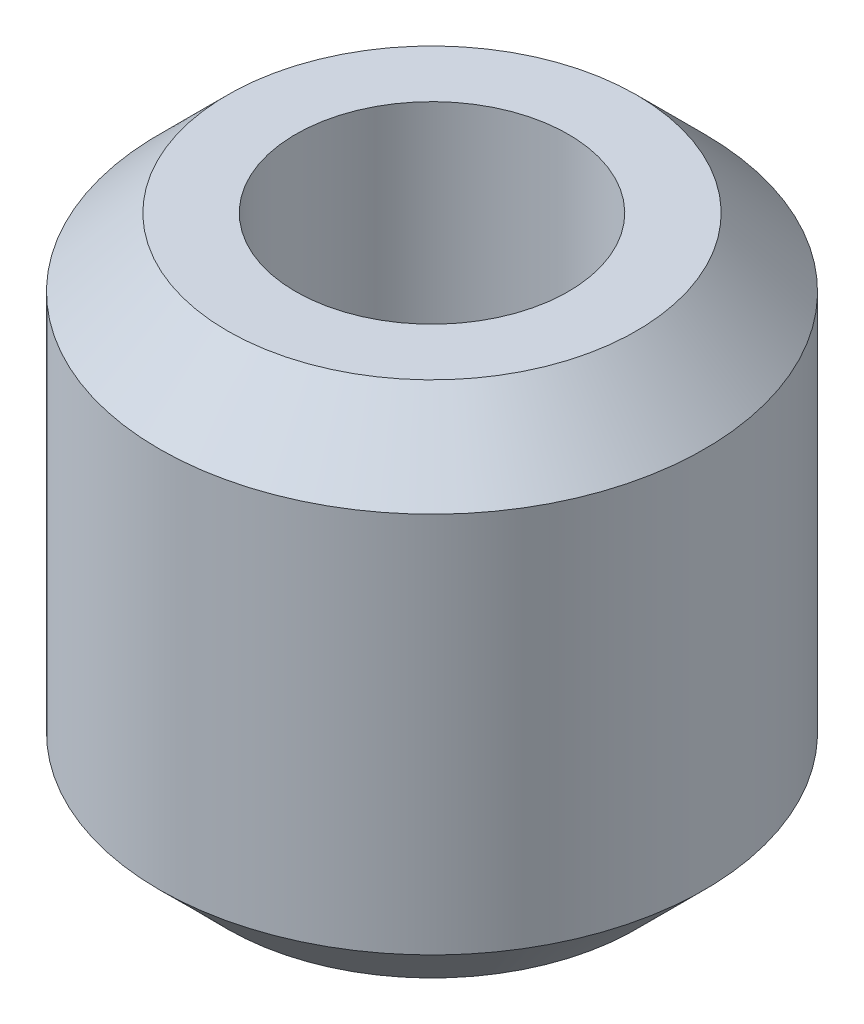
SolidWorks part; units mm, degrees
ref_plane "Front Plane" through (0, 0, 0) normal (0, 0, 1) x (1, 0, 0)
ref_plane "Top Plane" through (0, 0, 0) normal (0, 1, 0) x (1, 0, 0)
ref_plane "Right Plane" through (0, 0, 0) normal (1, 0, 0) x (0, 0, -1)
sketch "Sketch1" plane through (0, 0, 0) normal (0, 0, 1) x (1, 0, 0)
  line L0 (0, 14.3902) -> (0, -9.1311) construction
  line L1 (-10, 12.2993) -> (10, 12.2993)
  line L2 (-10, 12.2993) -> (-10, -6.7007)
  line L3 (-10, -6.7007) -> (10, -6.7007)
  line L4 (10, 12.2993) -> (10, -6.7007)
  line L5 (-5, 12.2993) -> (5, 12.2993)
  line L6 (-5, 12.2993) -> (-5, -6.7007)
  line L7 (-5, -6.7007) -> (5, -6.7007)
  line L8 (5, 12.2993) -> (5, -6.7007)
  dimension "D1" = 20
  dimension "D2" = 19
  dimension "D3" = 5
  dimension "D4" = 10
  dimension "D5" = 10
  dimension "D6" = 23.5213
revolve "Revolve1" add sketch "Sketch1" angle 360 about L0
chamfer "Chamfer1" distance 2.5 angle 45 1 edges at (0, 12.2993, 10)
chamfer "Chamfer2" distance 2.5 angle 45 1 edges at (0, -6.7007, 10)
